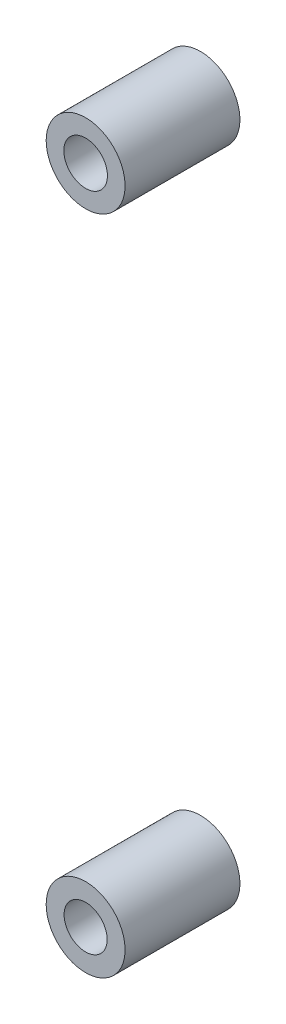
SolidWorks part; units mm, degrees
material "黄铜"
ref_plane "前视基准面" through (0, 0, 0) normal (0, 0, 1) x (1, 0, 0)
ref_plane "上视基准面" through (0, 0, 0) normal (0, 1, 0) x (1, 0, 0)
ref_plane "右视基准面" through (0, 0, 0) normal (1, 0, 0) x (0, 0, -1)
sketch "草图1" plane through (0, 0, 0) normal (0, 0, 1) x (1, 0, 0)
  circle A0 centre (-24.6985, 21.5378) radius 1.52
  circle A1 centre (-24.6985, 21.5378) radius 2.75
  circle A2 centre (-24.6985, -24.5622) radius 1.5
  circle A3 centre (-24.6985, -24.5622) radius 2.75
extrude "凸台-拉伸1" add sketch "草图1" against normal blind 8 from surface at -41.8004
